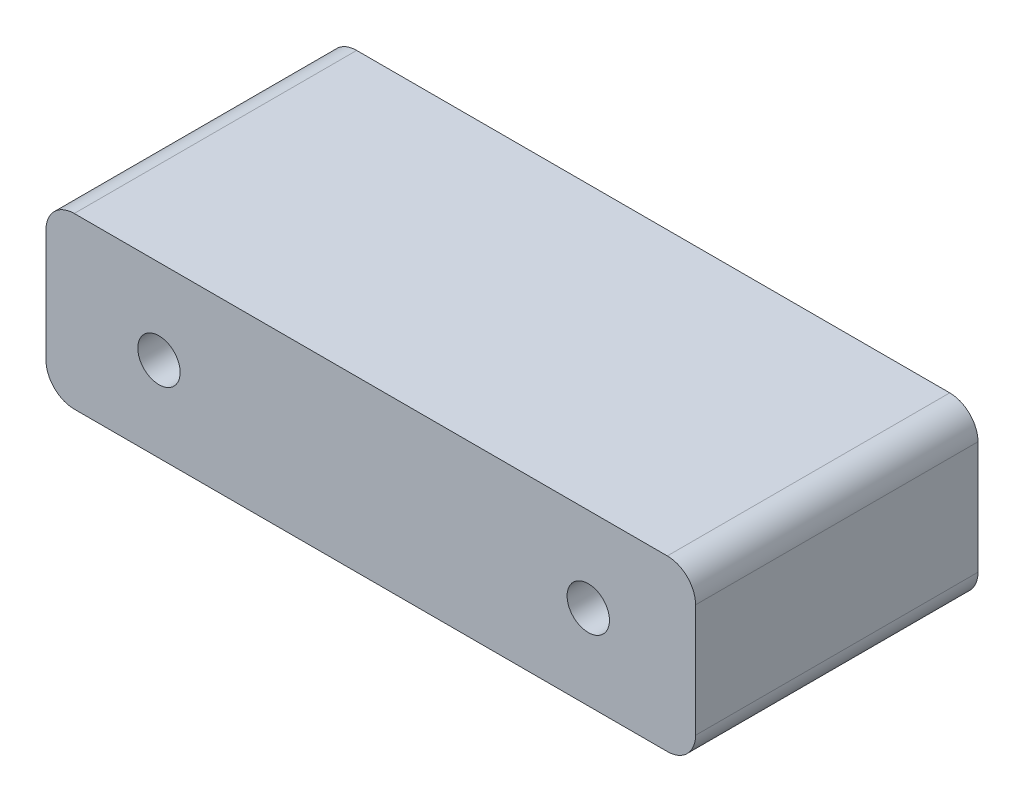
SolidWorks part; units mm, degrees
ref_plane "Alzado" through (0, 0, 0) normal (0, 0, 1) x (1, 0, 0)
ref_plane "Planta" through (0, 0, 0) normal (0, 1, 0) x (1, 0, 0)
ref_plane "Vista lateral" through (0, 0, 0) normal (1, 0, 0) x (0, 0, -1)
sketch "Croquis1" plane through (0, 0, 0) normal (0, 0, 1) x (1, 0, 0)
  line L0 (-2.3508, 0.3116) -> (12.8492, 0.3116) construction
  line L1 (-2.3508, 0.3116) -> (-2.3508, 3.3116) construction
  line L2 (-2.3508, 0.3116) -> (-2.3508, -2.6884) construction
  line L3 (-2.3508, -2.6884) -> (16.6492, -2.6884) construction
  line L4 (-2.3508, 3.3116) -> (-6.3508, 3.3116) construction
  line L6 (16.6492, -2.6884) -> (-6.3508, -2.6884)
  line L7 (16.6492, -2.6884) -> (16.6492, 3.3116)
  line L8 (16.6492, 3.3116) -> (-6.3508, 3.3116)
  line L9 (-6.3508, -2.6884) -> (-6.3508, 3.3116)
  circle A0 centre (-2.3508, 0.3116) radius 0.75
  circle A1 centre (12.8492, 0.3116) radius 0.75
  dimension "D2" = 1.5
  dimension "D3" = 1.5
  dimension "D1" = 15.2
  dimension "D4" = 3
  dimension "D5" = 3
  dimension "D6" = 19
  dimension "D7" = 4
extrude "Saliente-Extruir1" add sketch "Croquis1" along normal blind 10
fillet "Redondeo1" radius 1 4 edges at (16.6492, -2.6884, 5) (16.6492, 3.3116, 5) (-6.3508, -2.6884, 5) (-6.3508, 3.3116, 5)
